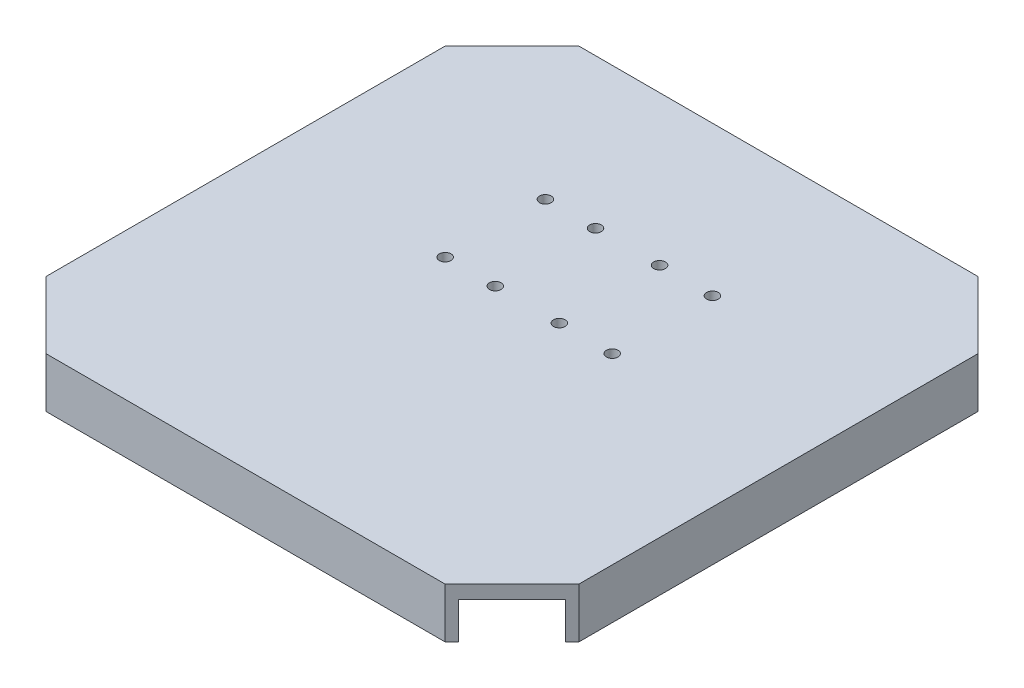
SolidWorks part; units mm, degrees
ref_plane "Front Plane" through (0, 0, 0) normal (0, 0, 1) x (1, 0, 0)
ref_plane "Top Plane" through (0, 0, 0) normal (0, 1, 0) x (1, 0, 0)
ref_plane "Right Plane" through (0, 0, 0) normal (1, 0, 0) x (0, 0, -1)
sketch "Sketch1" plane through (0, 0, 0) normal (0, 1, 0) x (1, 0, 0)
  line L0 (0, 139.5) -> (20, 159.5)
  line L1 (0, 0) -> (159.5, 0)
  line L2 (0, 0) -> (0, 159.5)
  line L3 (0, 159.5) -> (159.5, 159.5)
  line L4 (159.5, 0) -> (159.5, 159.5)
  line L5 (79.75, 159.5) -> (79.75, 0) construction
  line L6 (159.5, 79.75) -> (0, 79.75) construction
  line L7 (159.5, 139.5) -> (139.5, 159.5)
  line L8 (159.5, 20) -> (139.5, 0)
  line L9 (0, 20) -> (20, 0)
  dimension "D1" = 159.5
  dimension "D2" = 159.5
  dimension "D3" = 45
  dimension "D4" = 20
extrude "Boss-Extrude1" add sketch "Sketch1" along normal blind 15 contours L2 L9 L1 L8 L4 L7 L3 L0
sketch "Sketch5" plane through (0, 0, 0) normal (0, -1, 0) x (1, 0, 0)
  line L0 (0, -20) -> (0, -139.5) construction
  line L1 (2, -2) -> (157.5, -2)
  line L2 (2, -2) -> (2, -157.5)
  line L3 (2, -157.5) -> (157.5, -157.5)
  line L4 (157.5, -2) -> (157.5, -157.5)
  line L5 (20, 0) -> (139.5, 0) construction
  dimension "D1" = 2
  dimension "D2" = 2
  dimension "D3" = 155.5
extrude "Cut-Extrude3" cut sketch "Sketch5" against normal blind 11
sketch "Sketch7" plane through (0, 15, 0) normal (0, 1, 0) x (1, 0, 0)
  line L0 (79.75, 159.5) -> (79.75, 0) construction
  line L1 (20, 159.5) -> (139.5, 159.5) construction
  line L2 (20, 0) -> (139.5, 0) construction
  line L3 (0, 79.75) -> (159.5, 79.75) construction
  line L4 (0, 20) -> (0, 139.5) construction
  line L5 (159.5, 20) -> (159.5, 139.5) construction
  line L7 (49.75, 39.75) -> (109.75, 39.75)
  line L8 (49.75, 39.75) -> (49.75, 119.75)
  line L9 (49.75, 119.75) -> (109.75, 119.75)
  line L10 (109.75, 39.75) -> (109.75, 119.75)
  circle A0 centre (54.75, 114.75) radius 1.75
  circle A1 centre (104.75, 114.75) radius 1.75
  circle A4 centre (69.75, 114.75) radius 1.75
  circle A5 centre (88.9266, 114.75) radius 1.75
  circle A8 centre (54.75, 84.75) radius 1.75
  circle A9 centre (69.75, 84.75) radius 1.75
  circle A10 centre (88.9266, 84.75) radius 1.75
  circle A11 centre (104.75, 84.75) radius 1.75
  dimension "D5" = 5
  dimension "D7" = 3.5
  dimension "D8" = 10
  dimension "D9" = 3.5
  dimension "D10" = 3.5
  dimension "D11" = 2
  dimension "D1" = 30
  dimension "D2" = 60
  dimension "D3" = 80
  dimension "D4" = 40
  dimension "D6" = 5
extrude "Cut-Extrude4" cut sketch "Sketch7" against normal blind 2.5 contours A0 | A4 | A5 | A1 | A9 | A10 | A11 | A8
